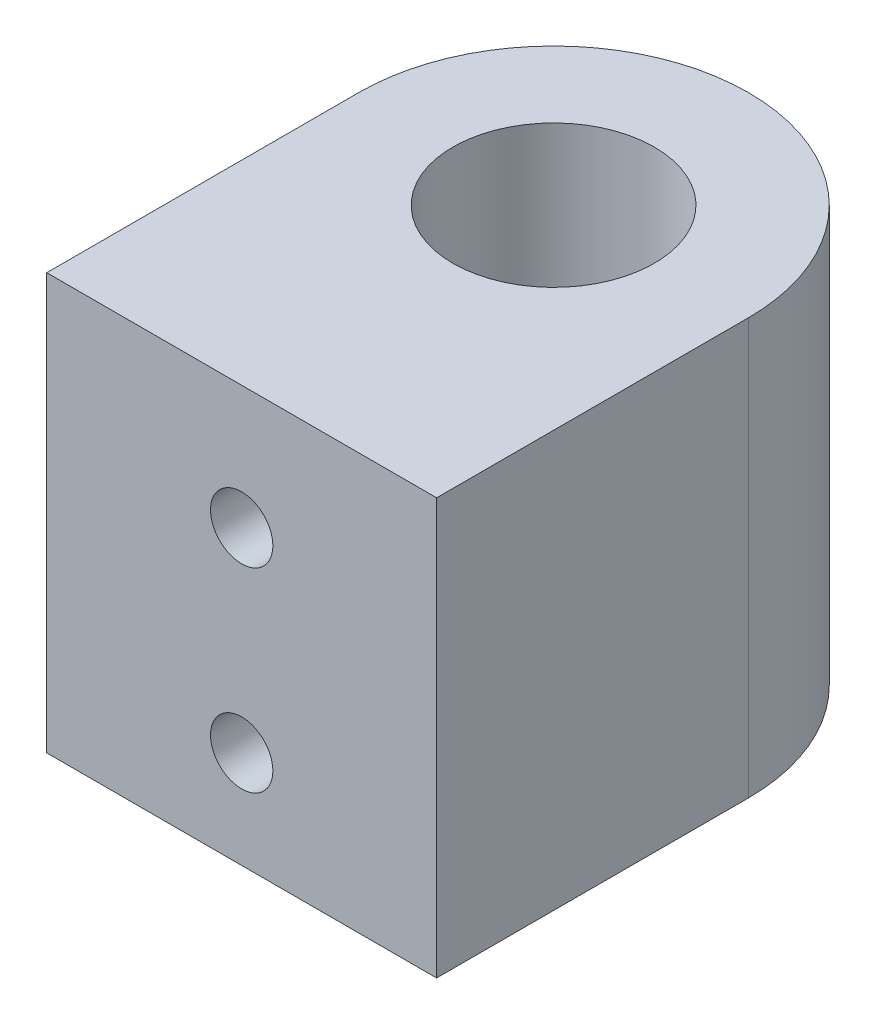
SolidWorks part; units mm, degrees
ref_plane "Front Plane" through (0, 0, 0) normal (0, 0, 1) x (1, 0, 0)
ref_plane "Top Plane" through (0, 0, 0) normal (0, 1, 0) x (1, 0, 0)
ref_plane "Right Plane" through (0, 0, 0) normal (1, 0, 0) x (0, 0, -1)
sketch "Sketch1" plane through (0, 0, 0) normal (0, 1, 0) x (1, 0, 0)
  line L2 (-15, 0) -> (-15, -24)
  line L3 (-15, -24) -> (15, -24)
  line L4 (15, 0) -> (15, -24)
  circle A0 centre (0, 0) radius 7.75
  arc A1 (15, 0) -> (-15, 0) centre (0, 0) ccw
  dimension "D1" = 15.5
  dimension "D2" = 30
  dimension "D3" = 24
extrude "Boss-Extrude1" add sketch "Sketch1" along normal blind 30
sketch "Sketch2" plane through (0, 0, 0) normal (0, -1, 0) x (1, 0, 0)
  circle A0 centre (0, 0) radius 7.75 construction
  circle A1 centre (0, 0) radius 7.75
  circle A2 centre (0, 0) radius 5
  dimension "D1" = 10
extrude "Boss-Extrude2" add sketch "Sketch2" against normal blind 7
sketch "Sketch3" plane through (0, 0, 24) normal (0, 0, 1) x (1, 0, 0)
  line L0 (0, 30) -> (0, 0) construction
  line L1 (-15, 30) -> (15, 30) construction
  line L2 (-15, 0) -> (15, 0) construction
  circle A0 centre (0, 22.5) radius 2.4
  circle A1 centre (0, 7.5) radius 2.4
  dimension "D1" = 4.8
  dimension "D2" = 4.8
  dimension "D3" = 15
  dimension "D4" = 7.5
extrude "Cut-Extrude1" cut sketch "Sketch3" against normal blind 27
sketch "Sketch4" plane through (0, 30, 0) normal (0, 1, 0) x (1, 0, 0)
  line L3 (-15, 0) -> (-15, -24)
  line L4 (-15, -24) -> (15, -24)
  line L5 (15, -24) -> (15, 0)
  line L6 (-15, 0) -> (-15, -24)
  line L7 (-15, -24) -> (15, -24)
  line L8 (15, -24) -> (15, 0)
  circle A0 centre (0, 0) radius 7.75 construction
  arc A1 (15, 0) -> (-15, 0) centre (0, 0) ccw
  arc A2 (15, 0) -> (-15, 0) centre (0, 0) ccw
  circle A3 centre (0, 0) radius 7.75
  dimension "D1" = 0
extrude "Boss-Extrude3" add sketch "Sketch4" along normal blind 2
